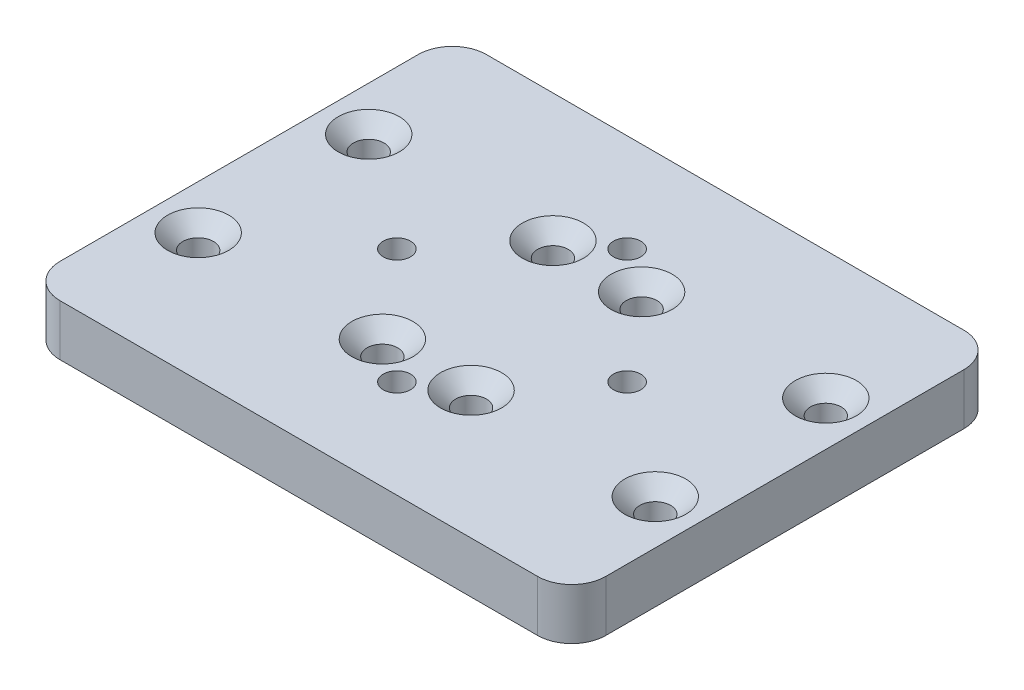
SolidWorks part; units mm, degrees
ref_plane "Płaszczyzna przednia" through (0, 0, 0) normal (0, 0, 1) x (1, 0, 0)
ref_plane "Płaszczyzna górna" through (0, 0, 0) normal (0, 1, 0) x (1, 0, 0)
ref_plane "Płaszczyzna prawa" through (0, 0, 0) normal (1, 0, 0) x (0, 0, -1)
sketch "Szkic1" plane through (0, 0, 0) normal (0, 1, 0) x (1, 0, 0)
  line L1 (-70, -62.5) -> (70, -62.5)
  line L2 (-80, -52.5) -> (-80, 52.5)
  line L3 (-70, 62.5) -> (70, 62.5)
  line L4 (80, -52.5) -> (80, 52.5)
  line L5 (-80, -62.5) -> (80, 62.5) construction
  line L6 (-80, 62.5) -> (80, -62.5) construction
  arc A0 (-70, -62.5) -> (-80, -52.5) centre (-70, -52.5) cw
  arc A1 (70, -62.5) -> (80, -52.5) centre (70, -52.5) ccw
  arc A2 (70, 62.5) -> (80, 52.5) centre (70, 52.5) cw
  arc A3 (-80, 52.5) -> (-70, 62.5) centre (-70, 52.5) cw
  point P0 (0, 0)
  dimension "D3" = 10
  dimension "D1" = 160
  dimension "D2" = 125
extrude "Dodanie-wyciągnięcie1" add sketch "Szkic1" along normal blind 15
sketch "Szkic2" plane through (0, 15, 0) normal (0, 1, 0) x (1, 0, 0)
  line L0 (-111.9141, 0) -> (104.9412, 0) construction
  line L1 (0, 83.2139) -> (0, -77.9424) construction
  line L3 (-40, 111.4393) -> (-40, -83.9517) construction
  circle A0 centre (-67, -25) radius 4
  circle A1 centre (-13, -25) radius 4
  dimension "D1" = 8
  dimension "D2" = 50
  dimension "D3" = 54
  dimension "D4" = 40
extrude "Wytnij-wyciągnięcie1" cut sketch "Szkic2" against normal through all both and the other way through all
mirror "Lustro1" about plane through (0, 0, 0) normal (0, 0, 1) of "Wytnij-wyciągnięcie1"
mirror "Lustro2" about plane through (0, 0, 0) normal (1, 0, 0) of "Lustro1", "Wytnij-wyciągnięcie1"
chamfer "Sfazowanie1" distance 0.5 angle 45 16 edges at (-67, 15, 21) (-67, 0, 29) (-13, 15, 21) (-13, 0, 21) (13, 15, 21) (13, 0, 21) (67, 15, 21) (67, 0, 29) (67, 15, -29) (67, 0, -29) (13, 15, -29) (13, 0, -21) (-13, 15, -29) (-13, 0, -21) (-67, 15, -29) (-67, 0, -29)
hole_wizard "Pogłębienie stożkowe pod M8 Wkręt z łbem stożkowym płaskim1" positions "Szkic3" profile "Szkic4" countersink size "M8" standard "ISO" end condition through all
sketch "Szkic3" plane through (0, 15, 0) normal (0, 1, 0) x (1, 0, 0)
  point P0 (-67, 25)
  point P3 (-13, 25)
  point P6 (-13, -25)
  point P9 (13, -25)
  point P12 (13, 25)
  point P15 (67, 25)
  point P18 (67, -25)
  point P21 (-67, -25)
sketch "Szkic4" plane through (-67, 15, -25) normal (1, 0, 0) x (0, 0, 1)
  line L0 (0, 0) -> (0, 15)
  line L1 (0, 15) -> (4.5, 15)
  line L2 (4.5, 15) -> (4.5, 4.46)
  line L3 (4.5, 4.46) -> (8.96, 0)
  line L5 (8.96, 0) -> (0, 0)
  line L6 (-4.5, 4.46) -> (-8.96, 0) construction
  line L11 (0, -6.35) -> (0, 107.95) construction
  dimension "Średnica otworu na wylot" = 9
  dimension "Głębokość otworu na wylot" = 15
  dimension "Średnica zewnętrznego pogłębienia stożkowego" = 17.92
  dimension "Kąt zewnętrznego pogłębienia stożkowego" = 90
sketch "Szkic5" plane through (0, 15, 0) normal (0, 1, 0) x (1, 0, 0)
  line L0 (0, 114.7312) -> (0, -116.9) construction
  line L1 (-112.2016, 0) -> (145.1212, 0) construction
  circle A0 centre (0, 33.75) radius 4
  circle A1 centre (33.75, 0) radius 4
  circle A2 centre (0, -33.75) radius 4
  circle A3 centre (-33.75, 0) radius 4
  point P7 (49.603, -3.7581)
  point P8 (0, 0)
  point P9 (0, 0)
  point P16 (0, 0)
  point P17 (0, 0)
  point P18 (0, 0)
  dimension "D1" = 8
  dimension "D2" = 67.5
  dimension "D3" = 4
extrude "Wytnij-wyciągnięcie2" cut sketch "Szkic5" against normal through all
